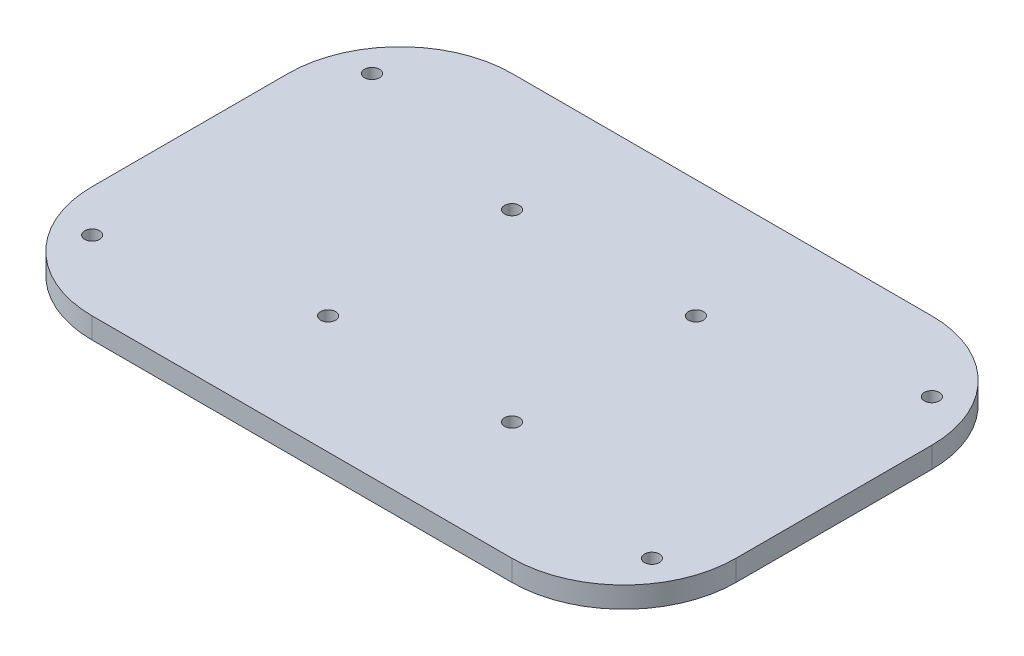
SolidWorks part; units mm, degrees
ref_plane "Front Plane" through (0, 0, 0) normal (0, 0, 1) x (1, 0, 0)
ref_plane "Top Plane" through (0, 0, 0) normal (0, 1, 0) x (1, 0, 0)
ref_plane "Right Plane" through (0, 0, 0) normal (1, 0, 0) x (0, 0, -1)
sketch "Sketch1" plane through (0, 0, 0) normal (0, 1, 0) x (1, 0, 0)
  line L1 (-47.625, -47.625) -> (47.625, -47.625)
  line L2 (-73.025, -22.225) -> (-73.025, 22.225)
  line L3 (-47.625, 47.625) -> (47.625, 47.625)
  line L4 (73.025, -22.225) -> (73.025, 22.225)
  arc A0 (47.625, -47.625) -> (73.025, -22.225) centre (47.625, -22.225) ccw
  arc A1 (-47.625, -47.625) -> (-73.025, -22.225) centre (-47.625, -22.225) cw
  arc A2 (-73.025, 22.225) -> (-47.625, 47.625) centre (-47.625, 22.225) cw
  arc A3 (47.625, 47.625) -> (73.025, 22.225) centre (47.625, 22.225) cw
  point P7 (46.2208, -44.2442)
  point P8 (73.025, -47.625)
  point P11 (-73.025, -47.625)
  point P16 (73.025, 47.625)
  dimension "D5" = 25.4
  dimension "D1" = 146.05
  dimension "D2" = 95.25
  dimension "D3" = 73.025
  dimension "D4" = 47.625
extrude "Boss-Extrude1" add sketch "Sketch1" along normal blind 4.7625
sketch "Sketch2" plane through (0, 4.7625, 0) normal (0, 1, 0) x (1, 0, 0)
  circle A0 centre (-63.5, -31.75) radius 1.7
  circle A1 centre (-63.5, 31.75) radius 1.7
  circle A2 centre (63.5, 31.75) radius 1.7
  circle A3 centre (63.5, -31.75) radius 1.7
  point P4 (-23.7587, 31.0607)
  point P7 (52.5307, 18.4184)
  point P10 (31.6056, -41.5232)
  point P13 (-41.24, -20.5981)
  dimension "D1" = 3.4
  dimension "D2" = 3.4
  dimension "D3" = 3.4
  dimension "D4" = 3.4
  dimension "D6" = 0
  dimension "D7" = 0
  dimension "D8" = 127
  dimension "D9" = 63.5
  dimension "D10" = 0
  dimension "D5" = 0
  dimension "D11" = 63.5
  dimension "D12" = 31.75
extrude "Cut-Extrude1" cut sketch "Sketch2" against normal through all
sketch "Sketch3" plane through (0, 4.7625, 0) normal (0, 1, 0) x (1, 0, 0)
  circle A1 centre (20.8597, 20.8597) radius 1.7
  circle A2 centre (-20.8597, 20.8597) radius 1.7
  circle A3 centre (-20.8597, -20.8597) radius 1.7
  circle A4 centre (20.8597, -20.8597) radius 1.7
  dimension "D2" = 3.4
  dimension "D3" = 3.4
  dimension "D4" = 3.4
  dimension "D5" = 3.4
extrude "Cut-Extrude2" cut sketch "Sketch3" against normal through all
